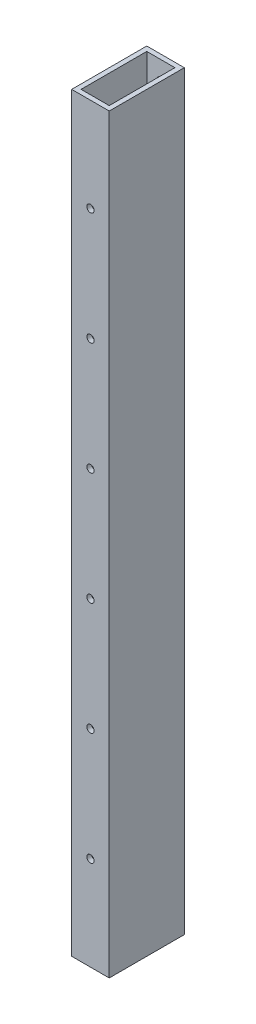
SolidWorks part; units mm, degrees
ref_plane "Front Plane" through (0, 0, 0) normal (0, 0, 1) x (1, 0, 0)
ref_plane "Top Plane" through (0, 0, 0) normal (0, 1, 0) x (1, 0, 0)
ref_plane "Right Plane" through (0, 0, 0) normal (1, 0, 0) x (0, 0, -1)
sketch "Sketch1" plane through (0, 0, 0) normal (0, 1, 0) x (1, 0, 0)
  line L0 (22.225, 3.175) -> (22.225, 47.625)
  line L1 (0, 0) -> (25.4, 0)
  line L2 (0, 0) -> (0, 50.8)
  line L3 (0, 50.8) -> (25.4, 50.8)
  line L4 (25.4, 0) -> (25.4, 50.8)
  line L5 (3.175, 47.625) -> (22.225, 47.625)
  line L6 (3.175, 3.175) -> (3.175, 47.625)
  line L7 (3.175, 3.175) -> (22.225, 3.175)
  dimension "D1" = 50.8
  dimension "D2" = 25.4
  dimension "D3" = 3.175
extrude "Boss-Extrude1" add sketch "Sketch1" along normal blind 508
sketch "Sketch2" plane through (0, 0, -50.8) normal (0, 0, -1) x (-1, 0, 0)
  circle A0 centre (-12.7, 12.7) radius 2.4638
  circle A1 centre (-12.7, 50.8) radius 2.4638
  circle A2 centre (-12.7, 177.8) radius 2.4638
  circle A3 centre (-12.7, 215.9) radius 2.4638
  circle A4 centre (-12.7, 241.3) radius 2.4638
  circle A5 centre (-12.7, 266.7) radius 2.4638
  circle A6 centre (-12.7, 292.1) radius 2.4638
  circle A7 centre (-12.7, 330.2) radius 2.4638
  circle A8 centre (-12.7, 457.2) radius 2.4638
  circle A9 centre (-12.7, 495.3) radius 2.4638
extrude "Cut-Extrude1" cut sketch "Sketch2" against normal up to next
sketch "Sketch3" plane through (0, 0, 0) normal (0, 0, 1) x (1, 0, 0)
  circle A0 centre (12.7, 63.5) radius 2.4638
  circle A1 centre (12.7, 139.7) radius 2.4638
  circle A2 centre (12.7, 215.9) radius 2.4638
  circle A3 centre (12.7, 292.1) radius 2.4638
  circle A4 centre (12.7, 368.3) radius 2.4638
  circle A5 centre (12.7, 444.5) radius 2.4638
extrude "Cut-Extrude2" cut sketch "Sketch3" against normal up to next
sketch "Sketch4" plane through (0, 0, 0) normal (-1, 0, 0) x (0, 0, 1)
  circle A0 centre (-38.1105, 96.6351) radius 2.5797
  circle A1 centre (-38.1105, 411.3649) radius 2.5797
  circle A2 centre (-12.7105, 411.3649) radius 2.5797
  circle A3 centre (-12.7105, 96.6351) radius 2.5797
  dimension "D1" = 5.1594
extrude "Cut-Extrude3" cut sketch "Sketch4" against normal up to next
